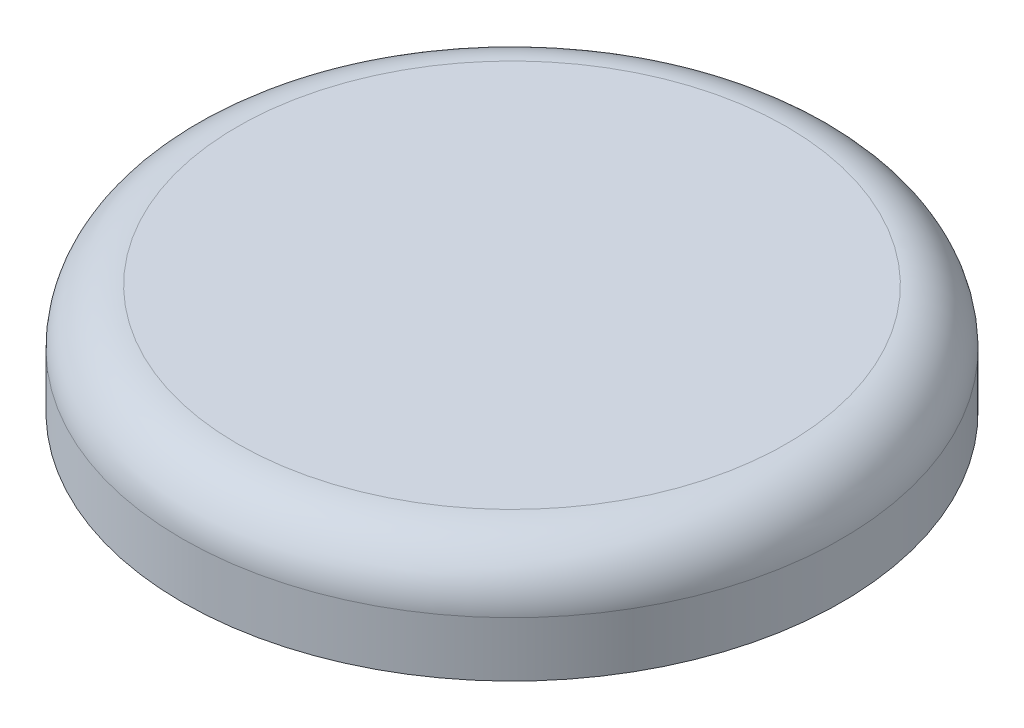
SolidWorks part; units mm, degrees
ref_plane "Front" through (0, 0, 0) normal (0, 0, 1) x (1, 0, 0)
ref_plane "Top" through (0, 0, 0) normal (0, 1, 0) x (1, 0, 0)
ref_plane "Right" through (0, 0, 0) normal (1, 0, 0) x (0, 0, -1)
sketch "Çizim1" plane through (0, 0, 0) normal (0, 1, 0) x (1, 0, 0)
  circle A0 centre (0, 0) radius 60
  dimension "D1" = 120
extrude "Yükseklik-Ekstrüzyon1" add sketch "Çizim1" along normal blind 20
fillet "Radyus1" radius 10 1 edges at (0, 20, 60)
